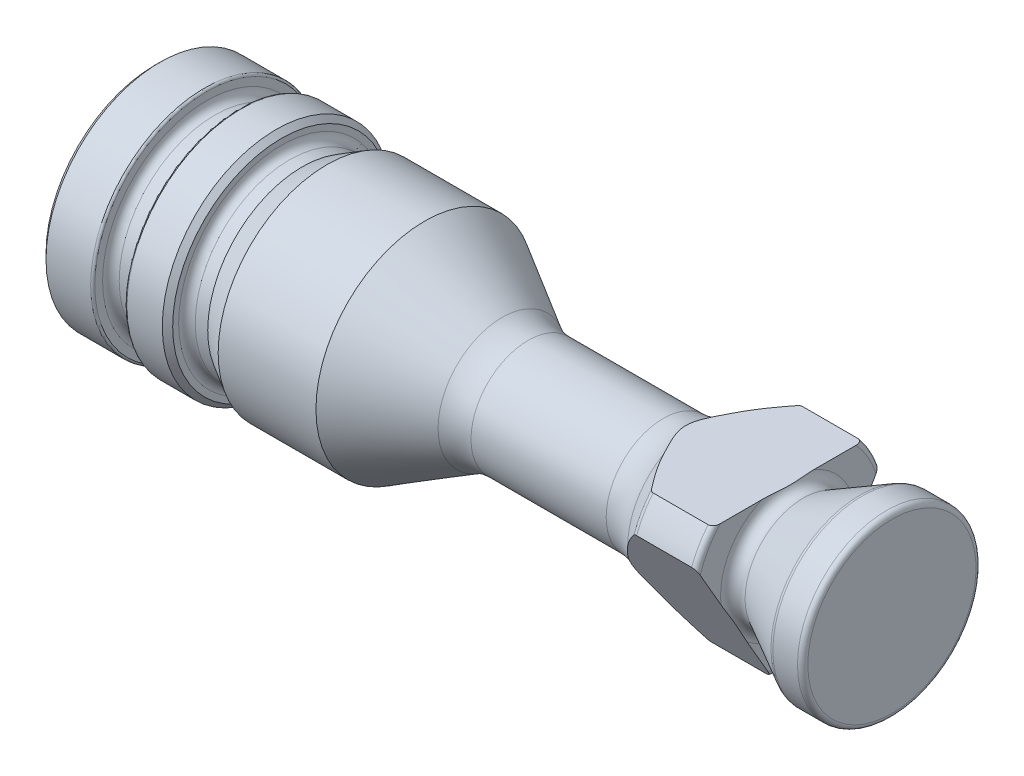
SolidWorks part; units mm, degrees
material "4140 H/T"
ref_plane "Front Plane" through (0, 0, 0) normal (0, 0, 1) x (1, 0, 0)
ref_plane "Top Plane" through (0, 0, 0) normal (0, 1, 0) x (1, 0, 0)
ref_plane "Right Plane" through (0, 0, 0) normal (1, 0, 0) x (0, 0, -1)
sketch "Sketch1" plane through (0, 0, 0) normal (0, 0, 1) x (1, 0, 0)
  line L1 (33.4567, 6.1699) -> (26, 10.475)
  line L2 (26, 10.475) -> (16.5816, 10.475)
  line L3 (16.5816, 10.475) -> (14.2, 9.1)
  line L4 (14.2, 9.1) -> (13, 9.1)
  line L5 (12.2, 9.9) -> (12.2, 10.975)
  line L6 (12.2, 10.975) -> (8.3, 10.975)
  line L7 (8.1, 10.775) -> (8.1, 10.025)
  line L8 (7.3, 9.225) -> (5.8, 9.225)
  line L9 (5, 10.025) -> (5, 10.775)
  line L10 (4.8, 10.975) -> (0, 10.975)
  line L11 (0, 10.975) -> (0, 0)
  line L12 (0, 0) -> (71, 0)
  line L13 (71, 0) -> (83.3329, 0) construction
  line L14 (35.9567, 5.5) -> (48.9753, 5.5)
  line L15 (52.4542, 6.9088) -> (54.8546, 9.2341)
  line L16 (55.2025, 9.375) -> (60.5, 9.375)
  line L17 (61, 8.875) -> (61, 6.5)
  line L19 (62.4747, 5.6199) -> (67.8889, 8.5401)
  line L20 (68.1262, 8.6) -> (70.5, 8.6)
  line L21 (71, 8.1) -> (71, 0)
  arc A0 (8.1, 10.025) -> (7.3, 9.225) centre (7.3, 10.025) cw
  arc A1 (5.8, 9.225) -> (5, 10.025) centre (5.8, 10.025) cw
  arc A2 (8.3, 10.975) -> (8.1, 10.775) centre (8.3, 10.775) ccw
  arc A3 (5, 10.775) -> (4.8, 10.975) centre (4.8, 10.775) ccw
  arc A4 (13, 9.1) -> (12.2, 9.9) centre (13, 9.9) cw
  arc A5 (62.4747, 5.6199) -> (61, 6.5) centre (62, 6.5) cw
  arc A6 (48.9753, 5.5) -> (52.4542, 6.9088) centre (48.9753, 10.5) ccw
  arc A7 (33.4567, 6.1699) -> (35.9567, 5.5) centre (35.9567, 10.5) ccw
  arc A8 (70.5, 8.6) -> (71, 8.1) centre (70.5, 8.1) cw
  arc A9 (67.8889, 8.5401) -> (68.1262, 8.6) centre (68.1262, 8.1) cw
  arc A10 (60.5, 9.375) -> (61, 8.875) centre (60.5, 8.875) cw
  arc A11 (54.8546, 9.2341) -> (55.2025, 9.375) centre (55.2025, 8.875) cw
  point P17 (8.1, 9.225)
  point P20 (5, 9.225)
  point P43 (51, 5.5)
  point P50 (68, 8.6)
  point P55 (55, 9.375)
  dimension "D13" = 0.8
  dimension "D14" = 0.2
  dimension "D15" = 0.8
  dimension "D21" = 1
  dimension "D22" = 11
  dimension "D25" = 5
  dimension "D26" = 0.5
  dimension "D1" = 26
  dimension "D2" = 21.95
  dimension "D3" = 18.45
  dimension "D4" = 3.1
  dimension "D5" = 5
  dimension "D6" = 12.2
  dimension "D7" = 20.95
  dimension "D8" = 18.2
  dimension "D9" = 30
  dimension "D10" = 2
  dimension "D11" = 30
  dimension "D12" = 11
  dimension "D16" = 18.75
  dimension "D17" = 3
  dimension "D18" = 16
  dimension "D19" = 20
  dimension "D20" = 71
  dimension "D23" = 10
  dimension "D24" = 17.2
revolve "Revolve1" add sketch "Sketch1" angle 360 about L13
cosmetic thread "Cosmetic Thread1" parameters "D2"=19.5
sketch "Sketch2" plane through (0, 0, 0) normal (-1, 0, 0) x (0, 0, 1)
  line L1 (-5, 5) -> (5, 5)
  line L2 (-5, 5) -> (-5, -5)
  line L3 (-5, -5) -> (5, -5)
  line L4 (5, 5) -> (5, -5)
  dimension "D1" = 10
  dimension "D2" = 10
  dimension "D3" = 5
  dimension "D4" = 5
extrude "Cut-Extrude1" cut sketch "Sketch2" against normal blind 10
chamfer "Chamfer2" distance 0.5 angle 45 1 edges at (0, 0, 10.975)
chamfer "Chamfer3" distance 0.5 angle 45 1 edges at (12.2, 0, 10.975)
sketch "Sketch3" plane through (0, 0, 0) normal (-1, 0, 0) x (0, 0, 1)
  line L0 (0, 0) -> (12.8316, 0) construction
  line L1 (0, 0) -> (0, 7.4258) construction
  circle A0 centre (3.8, 3.8) radius 1.75
  circle A1 centre (-3.8, 3.8) radius 1.75
  circle A2 centre (3.8, -3.8) radius 1.75
  circle A3 centre (-3.8, -3.8) radius 1.75
  dimension "D3" = 3.5
  dimension "D1" = 7.6
  dimension "D2" = 7.6
extrude "Cut-Extrude2" cut sketch "Sketch3" against normal up to surface (10 mm away) up to face at (10, 0, 0)
chamfer "Chamfer4" distance 0.5 angle 45 8 edges at (0, -5, 0) (0, 0, 5) (0, 5, 0) (0, 0, -5) (0, -5.0374, -5.0374) (0, -5.0374, 5.0374) (0, 5.0374, 5.0374) (0, 5.0374, -5.0374)
sketch "Sketch4" plane through (0, 0, 0) normal (-1, 0, 0) x (0, 0, 1)
  line L0 (-3.4805, 7.0929) -> (3.5995, 7.0929) construction
  line L1 (-5.6848, -8.0784) -> (5.337, -8.0784) construction
  text T1 "BG 008 517 87" font "Century Gothic" height 1.2
  line B0 (1.3723, 6.0464) -> (-0.5887, 6.0464)
  line B1 (1.0819, 6.4462) -> (-0.3614, 6.4462)
  line B2 (-0.5546, 6.1064) -> (-0.3955, 6.3862)
  line B3 (0.1661, 8.113) -> (-0.176, 8.113)
  line B4 (-0.5887, 9.4713) -> (0.1661, 8.113)
  line B5 (1.0819, 6.4462) -> (0.3712, 7.7346)
  line B6 (1.9488, 7.7346) -> (2.1281, 7.4247)
  line B7 (0.3737, 9.4713) -> (-0.5887, 9.4713)
  line B8 (1.7425, 8.113) -> (1.9488, 7.7346)
  line B9 (1.7425, 8.113) -> (1.2242, 8.9869)
  line B10 (-0.5887, 6.0464) -> (-2.0872, 6.0464)
  line B11 (-1.2448, 7.5279) -> (-2.0872, 6.0464)
  line B12 (1.8614, 7.7948) -> (1.7083, 8.053)
  line B13 (0.3737, 9.4113) -> (-0.4868, 9.4113)
  line B14 (-0.4868, 9.4113) -> (0.2347, 8.113)
  line B15 (-0.176, 8.053) -> (1.7083, 8.053)
  line B16 (-1.1934, 7.4969) -> (-1.9841, 6.1064)
  line B17 (-0.6236, 6.1064) -> (-1.9841, 6.1064)
  line B18 (0.3364, 7.7948) -> (1.8614, 7.7948)
  line B19 (-0.6236, 6.1064) -> (0.3364, 7.7948)
  line B20 (1.8795, 7.7346) -> (2.0768, 7.3935)
  line B21 (1.3723, 6.1064) -> (-0.5546, 6.1064)
  line B22 (0.2347, 8.113) -> (1.6727, 8.113)
  line B23 (1.6727, 8.113) -> (1.1726, 8.9563)
  line B24 (1.1835, 6.3862) -> (-0.3955, 6.3862)
  line B25 (1.1835, 6.3862) -> (0.4397, 7.7346)
  line B26 (0.4397, 7.7346) -> (1.8795, 7.7346)
  line B27 (-0.3614, 6.4462) -> (0.3712, 7.7346)
  arc B28 (1.2242, 8.9869) -> (0.3737, 9.4713) centre (0.3737, 8.4825) ccw
  arc B29 (1.3723, 6.0464) -> (2.1281, 7.4247) centre (1.3723, 6.9428) ccw
  arc B30 (-0.176, 8.113) -> (-1.2448, 7.5279) centre (-0.176, 6.8442) ccw
  arc B31 (1.1726, 8.9563) -> (0.3737, 9.4113) centre (0.3737, 8.4825) ccw
  arc B32 (-0.176, 8.053) -> (-1.1934, 7.4969) centre (-0.176, 6.8442) ccw
  arc B33 (1.3723, 6.1064) -> (2.0768, 7.3935) centre (1.3723, 6.9428) ccw
  dimension "D1" = 7.0929
  dimension "D2" = 8.0784
sketch_block_instance "SKETCH LOGO-1"
sketch_block "SKETCH LOGO" parameters "D1"=29.059, "D2"=11.4163, "D3"=29.624, "D4"=6.8884
extrude "Cut-Extrude3" cut sketch "Sketch4" against normal blind 0.01
ref_plane "Plane1" through (48.9753, 0, 0) normal (1, 0, 0) x (0, 0, -1)
sketch "Sketch5" plane through (48.9753, 0, 0) normal (1, 0, 0) x (0, 0, -1)
  line L0 (0, 0) -> (14.3782, 0) construction
  line L1 (0, 0) -> (0, 16.195) construction
  line L3 (-8.5864, 12.715) -> (8.5864, 12.715)
  line L4 (-8.5864, 12.715) -> (-8.5864, 6)
  line L5 (-8.5864, 6) -> (8.5864, 6)
  line L6 (8.5864, 12.715) -> (8.5864, 6)
  circle A0 centre (0, 0) radius 9.375 construction
  circle A1 centre (0, 0) radius 10.475 construction
  circle A3 centre (0, 0) radius 9.375 construction
  dimension "D1" = 6
  dimension "D2" = 6.715
  dimension "D4" = 15.375
extrude "Cut-Extrude4" cut sketch "Sketch5" along normal blind 13
pattern_circular "CirPattern1" count 3 over 360 about axis through (0, 0, 0) along (1, 0, 0) of "Cut-Extrude4"
equation "\"D1@Sketch3\" = \"D2@Sketch3\""
